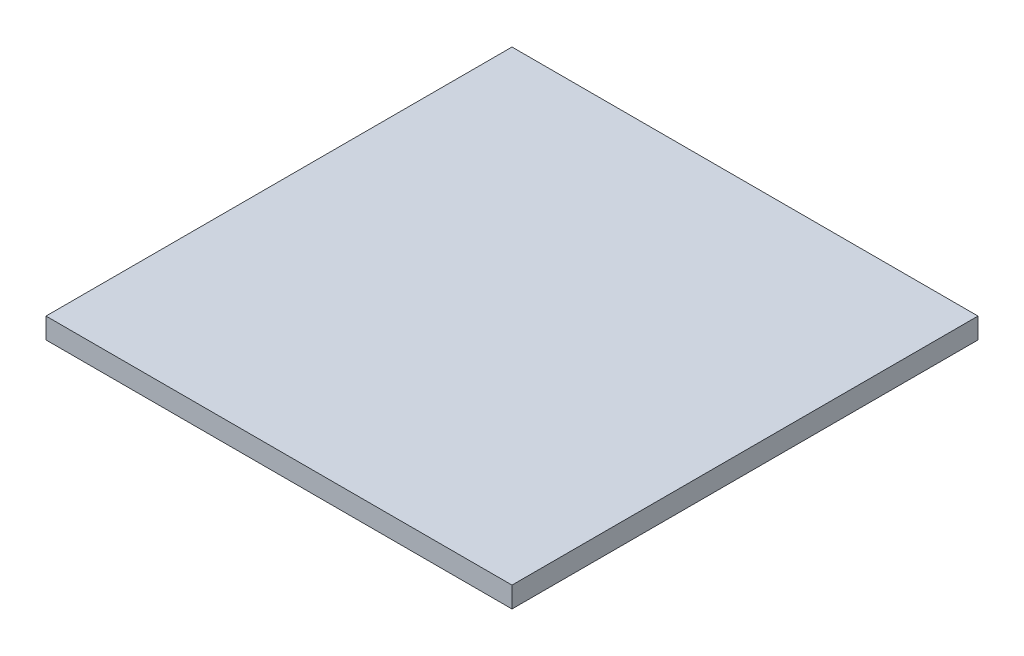
SolidWorks part; units mm, degrees
ref_plane "前视基准面" through (0, 0, 0) normal (0, 0, 1) x (1, 0, 0)
ref_plane "上视基准面" through (0, 0, 0) normal (0, 1, 0) x (1, 0, 0)
ref_plane "右视基准面" through (0, 0, 0) normal (1, 0, 0) x (0, 0, -1)
sketch "草图1" plane through (0, 0, 0) normal (0, 1, 0) x (1, 0, 0)
  line L1 (-81.3025, 49.3487) -> (98.6975, 49.3487)
  line L2 (-81.3025, 49.3487) -> (-81.3025, -130.6513)
  line L3 (-81.3025, -130.6513) -> (98.6975, -130.6513)
  line L4 (98.6975, 49.3487) -> (98.6975, -130.6513)
  dimension "D1" = 180
  dimension "D2" = 180
extrude "凸台-拉伸1" add sketch "草图1" along normal blind 8
